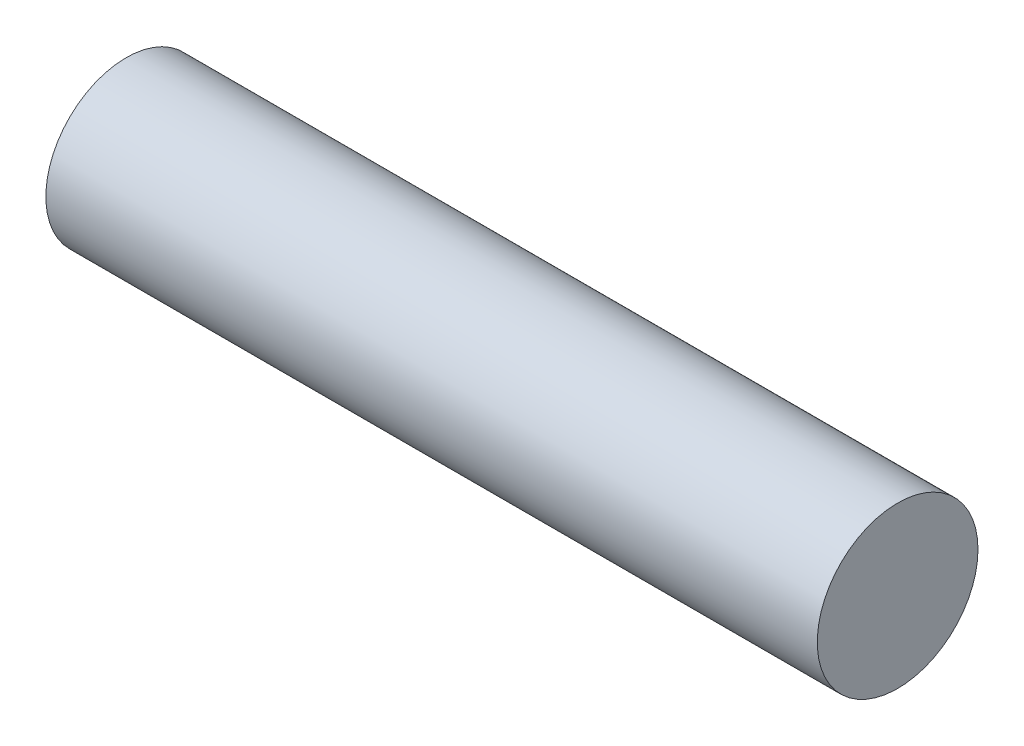
SolidWorks part; units mm, degrees
ref_plane "Front Plane" through (0, 0, 0) normal (0, 0, 1) x (1, 0, 0)
ref_plane "Top Plane" through (0, 0, 0) normal (0, 1, 0) x (1, 0, 0)
ref_plane "Right Plane" through (0, 0, 0) normal (1, 0, 0) x (0, 0, -1)
sketch "Sketch1" plane through (0, 0, 0) normal (1, 0, 0) x (0, 0, -1)
  circle A0 centre (0, 0) radius 1.5875
  dimension "D1" = 3.175
extrude "Boss-Extrude1" add sketch "Sketch1" along normal mid plane 15.24
